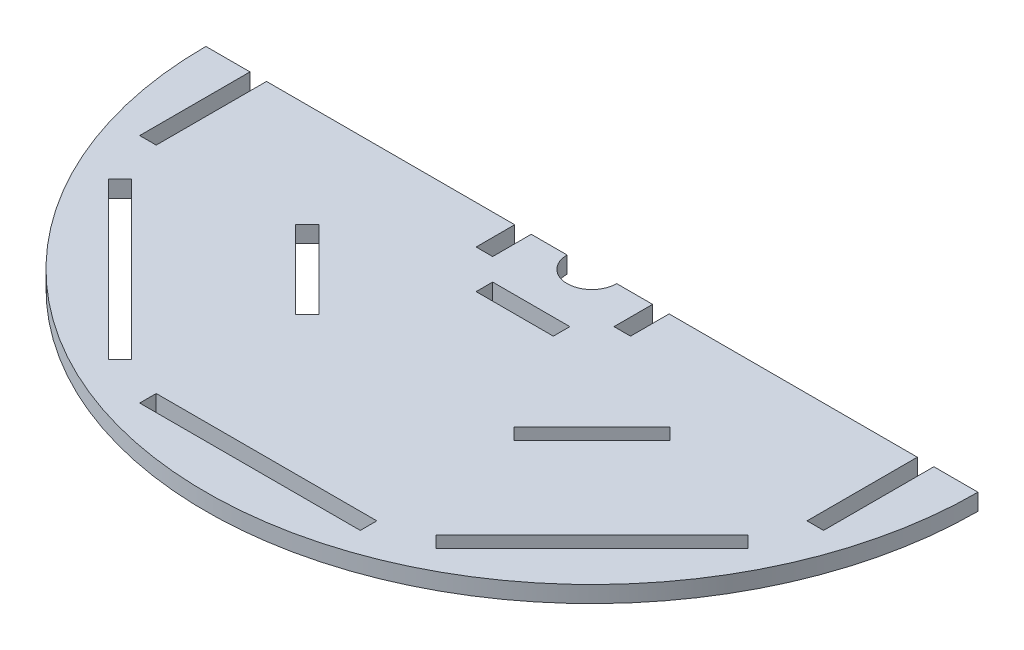
SolidWorks part; units mm, degrees
ref_plane "Alzado" through (0, 0, 0) normal (0, 0, 1) x (1, 0, 0)
ref_plane "Planta" through (0, 0, 0) normal (0, 1, 0) x (1, 0, 0)
ref_plane "Vista lateral" through (0, 0, 0) normal (1, 0, 0) x (0, 0, -1)
sketch "Croquis1" plane through (0, 0, 0) normal (0, 1, 0) x (1, 0, 0)
  line L0 (-59, 0) -> (-17, 0)
  line L1 (-11, 0) -> (-4.5, 0)
  line L2 (4.5, 0) -> (11, 0)
  line L3 (17, 0) -> (59, 0)
  line L4 (62, 0) -> (70, 0)
  line L5 (-14, -7) -> (-14, 0)
  line L7 (-70, 0) -> (-62, 0)
  line L8 (14, -7) -> (11, -7)
  line L9 (11, -7) -> (11, 0)
  line L10 (-17, 0) -> (-14, 0)
  line L12 (14, 0) -> (17, 0)
  line L13 (-14, -7) -> (-11, -7)
  line L14 (-11, -7) -> (-11, 0)
  line L15 (14, -7) -> (14, 0)
  line L16 (-7, -14) -> (7, -14)
  line L18 (7, -11) -> (7, -14)
  line L19 (0, -11) -> (7, -11)
  line L21 (-7, -14) -> (-7, -11)
  line L22 (-7, -11) -> (0, -11)
  line L35 (24.7487, -24.7487) -> (17.6777, -31.8198)
  line L36 (17.6777, -31.8198) -> (19.799, -33.9411)
  line L37 (19.799, -33.9411) -> (33.9411, -19.799)
  line L38 (31.8198, -17.6777) -> (33.9411, -19.799)
  line L39 (24.7487, -24.7487) -> (31.8198, -17.6777)
  line L40 (-24.7487, -24.7487) -> (-31.8198, -17.6777)
  line L52 (59, -20) -> (59, 0)
  line L55 (62, 0) -> (62, -20)
  line L56 (62, -20) -> (59, -20)
  line L57 (27.5772, -55.8614) -> (55.8614, -27.5772)
  line L58 (55.8614, -27.5772) -> (57.9828, -29.6985)
  line L59 (57.9828, -29.6985) -> (43.8406, -43.8406)
  line L60 (43.8406, -43.8406) -> (29.6985, -57.9828)
  line L61 (29.6985, -57.9828) -> (27.5772, -55.8614)
  line L62 (-20, -59) -> (20, -59)
  line L63 (20, -59) -> (20, -62)
  line L64 (20, -62) -> (0, -62)
  line L65 (0, -62) -> (-20, -62)
  line L66 (-20, -62) -> (-20, -59)
  line L67 (-55.8614, -27.5772) -> (-27.5772, -55.8614)
  line L68 (-27.5772, -55.8614) -> (-29.6985, -57.9828)
  line L69 (-29.6985, -57.9828) -> (-43.8406, -43.8406)
  line L70 (-43.8406, -43.8406) -> (-57.9828, -29.6985)
  line L71 (-57.9828, -29.6985) -> (-55.8614, -27.5772)
  line L72 (-59, 0) -> (-59, -20)
  line L73 (-59, -20) -> (-62, -20)
  line L74 (-62, -20) -> (-62, 0)
  line L82 (-31.8198, -17.6777) -> (-33.9411, -19.799)
  line L83 (-33.9411, -19.799) -> (-19.799, -33.9411)
  line L84 (-17.6777, -31.8198) -> (-19.799, -33.9411)
  line L85 (-24.7487, -24.7487) -> (-17.6777, -31.8198)
  arc A1 (-4.5, 0) -> (4.5, 0) centre (0, 0) ccw
  arc A2 (-70, 0) -> (70, 0) centre (0, 0) ccw
  point P47 (0, 0)
  point P88 (0, 0)
  point P93 (0, 0)
extrude "Saliente-Extruir1" add sketch "Croquis1" along normal blind 3
